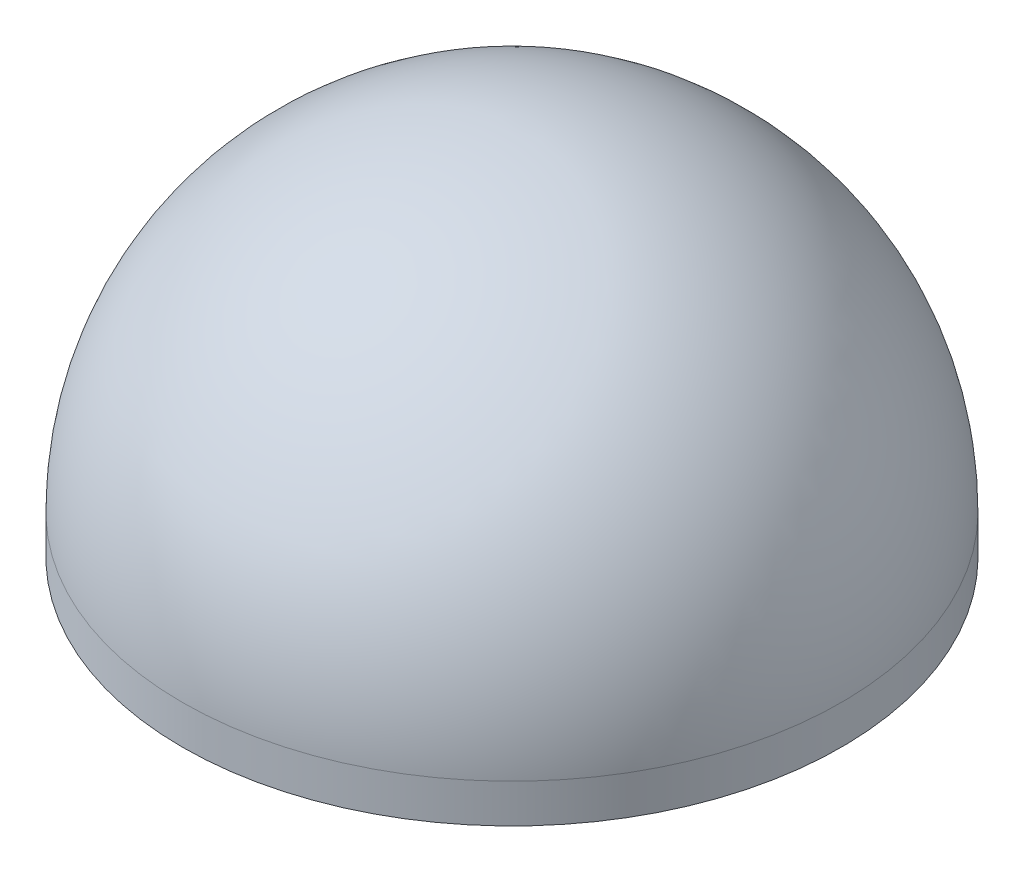
SolidWorks part; units mm, degrees
material "Natural Rubber"
ref_plane "Front Plane" through (0, 0, 0) normal (0, 0, 1) x (1, 0, 0)
ref_plane "Top Plane" through (0, 0, 0) normal (0, 1, 0) x (1, 0, 0)
ref_plane "Right Plane" through (0, 0, 0) normal (1, 0, 0) x (0, 0, -1)
sketch "Sketch1" plane through (0, 0, 0) normal (0, 1, 0) x (1, 0, 0)
  circle A0 centre (0, 0) radius 17
  dimension "D1" = 34
extrude "Boss-Extrude1" add sketch "Sketch1" along normal blind 2
sketch "Sketch2" plane through (0, 2, 0) normal (0, 1, 0) x (1, 0, 0)
  line L0 (-17, 0) -> (17, 0)
  arc A0 (-17, 0) -> (17, 0) centre (0, 0) cw
  circle A1 centre (0, 0) radius 17 construction
revolve "Revolve1" add sketch "Sketch2" angle 180 about L0
sketch "Sketch3" plane through (0, 0, 0) normal (0, -1, 0) x (1, 0, 0)
  circle A0 centre (0, 0) radius 11
  dimension "D1" = 22
extrude "Cut-Extrude1" cut sketch "Sketch3" against normal blind 4
